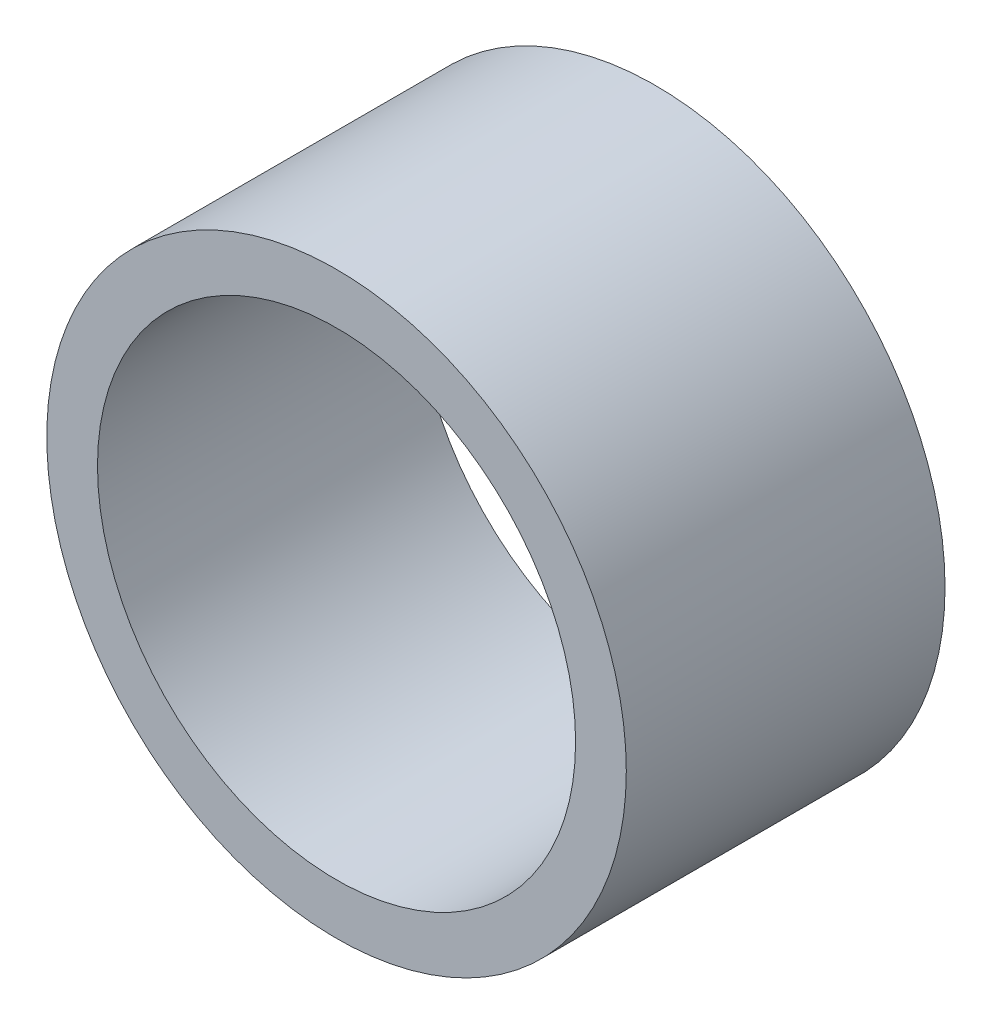
SolidWorks part; units mm, degrees
ref_plane "Alzado" through (0, 0, 0) normal (0, 0, 1) x (1, 0, 0)
ref_plane "Planta" through (0, 0, 0) normal (0, 1, 0) x (1, 0, 0)
ref_plane "Vista lateral" through (0, 0, 0) normal (1, 0, 0) x (0, 0, -1)
sketch "Croquis1" plane through (0, 0, 0) normal (0, 0, 1) x (1, 0, 0)
  line L0 (-22.8475, -2.9184) -> (-26.3475, -2.9184) construction
  circle A0 centre (-6.3475, -2.9184) radius 16.5
  circle A1 centre (-6.3475, -2.9184) radius 20
  dimension "D1" = 33
  dimension "D2" = 40
  dimension "D3" = 6.3475
  dimension "D4" = 2.9184
extrude "Saliente-Extruir1" add sketch "Croquis1" against normal blind 18.25 and the other way blind 3.75
